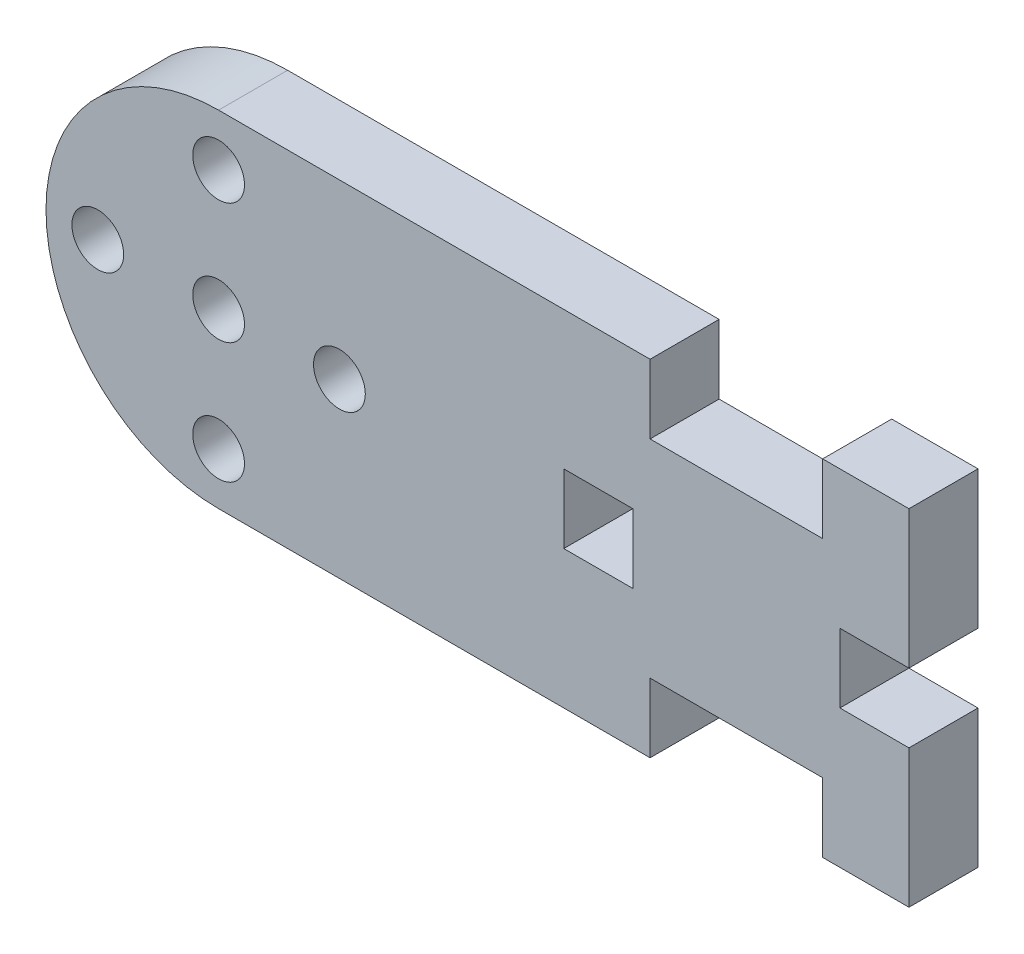
SolidWorks part; units mm, degrees
ref_plane "Спереди" through (0, 0, 0) normal (0, 0, 1) x (1, 0, 0)
ref_plane "Сверху" through (0, 0, 0) normal (0, 1, 0) x (1, 0, 0)
ref_plane "Справа" through (0, 0, 0) normal (1, 0, 0) x (0, 0, -1)
other "Configuration Table"
sketch "Эскиз1" plane through (0, 0, 0) normal (0, 0, 1) x (1, 0, 0)
  line L0 (-56.816, 0) -> (55, 0) construction
  line L1 (47, -12.5) -> (55, -12.5)
  line L3 (47, 12.5) -> (55, 12.5)
  line L5 (0, 10) -> (47, 10)
  line L6 (47, 10) -> (47, 12.5)
  line L7 (55, 12.5) -> (55, -12.5) construction
  line L8 (0, -10) -> (47, -10)
  line L9 (47, -10) -> (47, -12.5)
  line L11 (55, 12.5) -> (55, -12.5)
  arc A0 (0, 10) -> (0, -10) centre (0, 0) ccw
  circle A1 centre (49, 10.5) radius 1
  circle A4 centre (49, -10.5) radius 1
  circle A5 centre (0, 0) radius 1.5
  circle A7 centre (0, 0) radius 7 construction
  circle A8 centre (0, 7) radius 1.5
  circle A9 centre (7, 0) radius 1.5
  circle A10 centre (0, -7) radius 1.5
  circle A11 centre (-7, 0) radius 1.5
  point P6 (55, 0)
  point P8 (0, 0)
  point P13 (39.9395, 10.5)
  point P29 (0, 0)
  dimension "D3" = 20
  dimension "D2" = 2
  dimension "D6" = 3
  dimension "D10" = 2
  dimension "D4" = 3
  dimension "D9" = 14
  dimension "D1" = 8
  dimension "D5" = 21
  dimension "D7" = 55
  dimension "D8" = 4
  dimension "D11" = 25
extrude "Бобышка-Вытянуть1" add sketch "Эскиз1" along normal blind 4
sketch "Эскиз2" plane through (0, 0, 4) normal (0, 0, 1) x (1, 0, 0)
  line L0 (25, 6) -> (35, 6)
  line L1 (35, 6) -> (35, 10)
  line L3 (35, 10) -> (25, 10)
  line L4 (25, 10) -> (25, 6)
  line L5 (25, -6) -> (35, -6)
  line L6 (35, -6) -> (35, -10)
  line L8 (35, -10) -> (25, -10)
  line L9 (25, -10) -> (25, -6)
  line L10 (20, -2) -> (20, 2)
  line L11 (20, 2) -> (24, 2)
  line L12 (24, 2) -> (24, -2)
  line L13 (24, -2) -> (20, -2)
  line L23 (36, -2) -> (40, -2)
  line L24 (36, 2) -> (36, -2)
  line L25 (40, 2) -> (36, 2)
  line L26 (30, 10) -> (30, -10) construction
  line L28 (40, 2) -> (40, 17.4956)
  line L29 (40, 17.4956) -> (59.0662, 17.4956)
  line L30 (59.0662, 17.4956) -> (59.0662, -18.4879)
  line L31 (59.0662, -18.4879) -> (40, -18.4879)
  line L32 (40, -18.4879) -> (40, -2)
  point P23 (40, 1.798)
extrude "Вырез-Вытянуть3" cut sketch "Эскиз2" against normal blind 10
